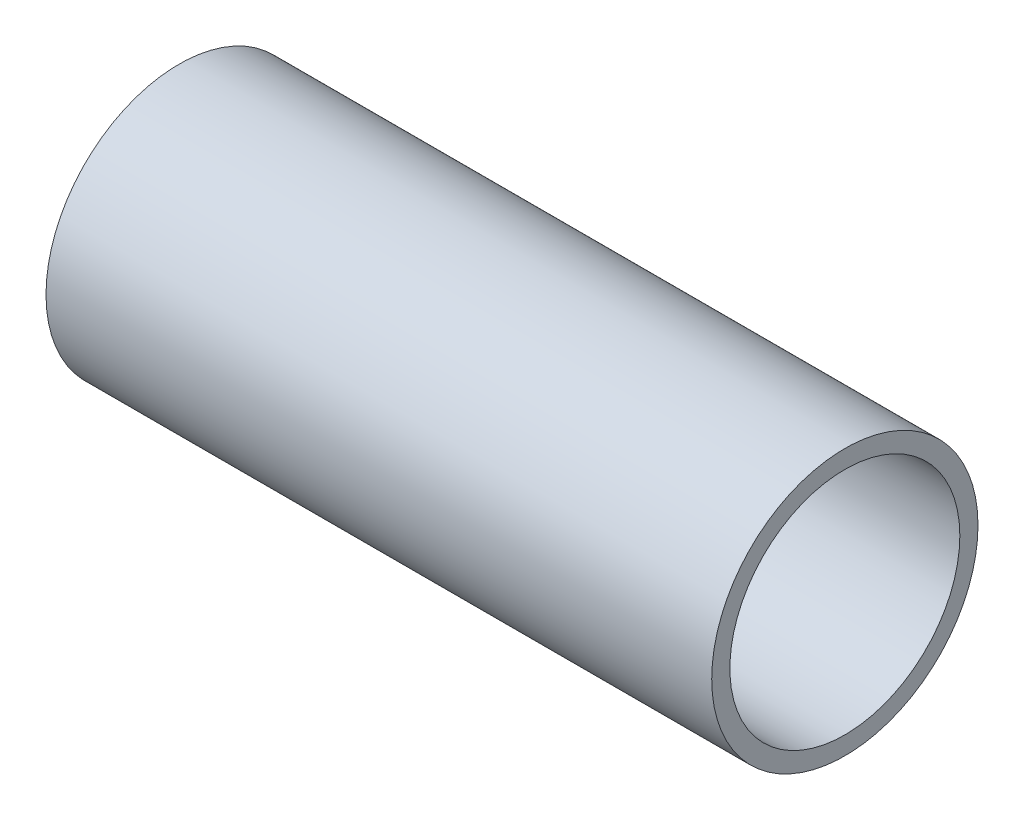
SolidWorks part; units mm, degrees
material "PVC 0.007 Plasticized"
ref_plane "Front Plane" through (0, 0, 0) normal (0, 0, 1) x (1, 0, 0)
ref_plane "Top Plane" through (0, 0, 0) normal (0, 1, 0) x (1, 0, 0)
ref_plane "Right Plane" through (0, 0, 0) normal (1, 0, 0) x (0, 0, -1)
sketch "Sketch1" plane through (0, 0, 0) normal (1, 0, 0) x (0, 0, -1)
  circle A0 centre (0, 0) radius 11
  circle A1 centre (0, 0) radius 9.5
  dimension "D1" = 1.5
extrude "Boss-Extrude1" add sketch "Sketch1" along normal blind 55
